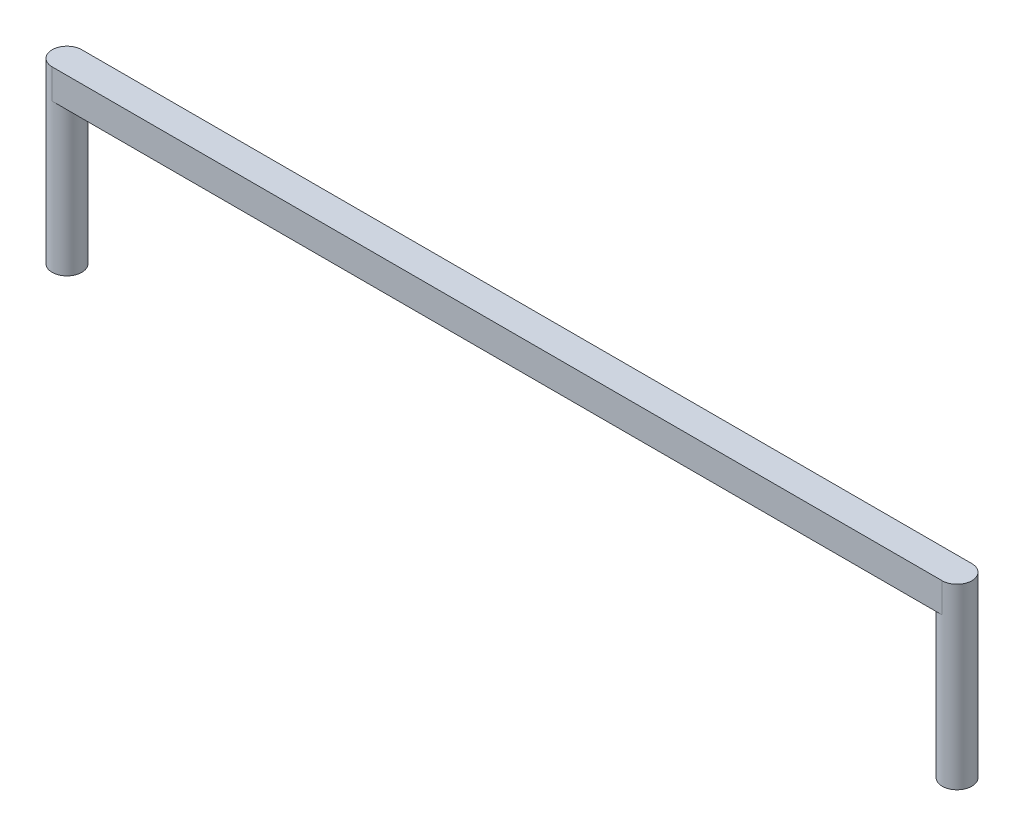
SolidWorks part; units mm, degrees
ref_plane "Alzado" through (0, 0, 0) normal (0, 0, 1) x (1, 0, 0)
ref_plane "Planta" through (0, 0, 0) normal (0, 1, 0) x (1, 0, 0)
ref_plane "Vista lateral" through (0, 0, 0) normal (1, 0, 0) x (0, 0, -1)
sketch "Croquis1" plane through (0, -13.655, 0) normal (0, 1, 0) x (1, 0, 0)
  line L0 (-15.3939, -34.4647) -> (44.6061, -34.4647) construction
  line L1 (-15.3939, -33.4647) -> (44.6061, -33.4647)
  line L3 (44.6061, -35.4647) -> (-15.3939, -35.4647)
  arc A2 (-15.3939, -33.4647) -> (-15.3939, -35.4647) centre (-15.3939, -34.4647) ccw
  arc A3 (44.6061, -35.4647) -> (44.6061, -33.4647) centre (44.6061, -34.4647) ccw
  dimension "D1" = 2
  dimension "D2" = 2
  dimension "D3" = 60
extrude "Saliente-Extruir1" add sketch "Croquis1" along normal blind 2 contours L3 A2 L1 A3
sketch "Croquis2" plane through (0, -11.655, 0) normal (0, 1, 0) x (1, 0, 0)
  circle A3 centre (-15.3939, -34.4647) radius 1
  circle A4 centre (44.6061, -34.4647) radius 1
  dimension "D1" = 2
  dimension "D2" = 2
extrude "Saliente-Extruir2" add sketch "Croquis2" against normal blind 12
